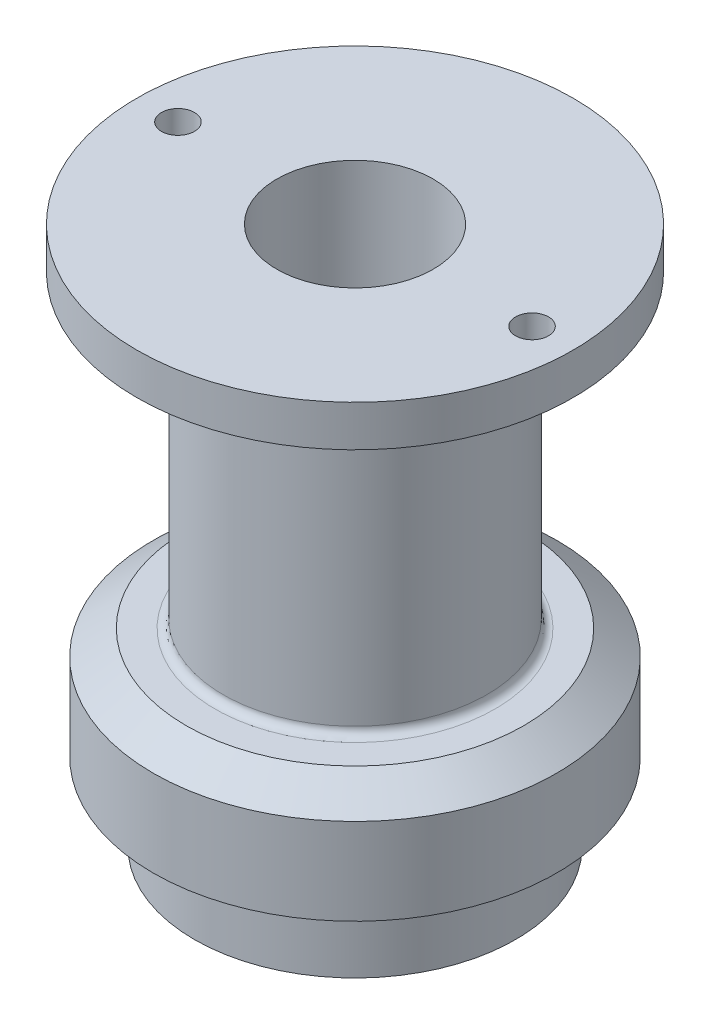
SolidWorks part; units mm, degrees
ref_plane "Front Plane" through (0, 0, 0) normal (0, 0, 1) x (1, 0, 0)
ref_plane "Top Plane" through (0, 0, 0) normal (0, 1, 0) x (1, 0, 0)
ref_plane "Right Plane" through (0, 0, 0) normal (1, 0, 0) x (0, 0, -1)
sketch "Sketch1" plane through (0, 0, 0) normal (0, 0, 1) x (1, 0, 0)
  line L0 (13.5, 0) -> (19.5, 0)
  line L1 (19.5, 0) -> (19.5, 8)
  line L2 (19.5, 8) -> (18, 8)
  line L3 (18, 8) -> (18, 9.5)
  line L4 (18, 9.5) -> (24.5, 9.5)
  line L5 (24.5, 9.5) -> (24.5, 20)
  line L6 (20.5, 23) -> (17, 23)
  line L7 (16, 24) -> (16, 59.5)
  line L8 (17, 60.5) -> (26.5, 60.5)
  line L9 (24.5, 20) -> (20.5, 23)
  line L10 (26.5, 60.5) -> (26.5, 65.5)
  line L11 (26.5, 65.5) -> (9.5, 65.5)
  line L12 (9.5, 65.5) -> (9.5, 48)
  line L13 (9.5, 48) -> (6.5, 44.5)
  line L14 (0, 0) -> (0, 87.6329) construction
  line L15 (6.5, 44.5) -> (6.5, 37.5)
  line L16 (7, 37) -> (7, 17)
  line L17 (7, 37) -> (6.5, 37.5)
  line L18 (6.5, 16.5) -> (6.5, 8)
  line L19 (7, 17) -> (6.5, 16.5)
  line L20 (6.5, 8) -> (13.5, 8)
  line L21 (13.5, 8) -> (13.5, 0)
  arc A0 (17, 23) -> (16, 24) centre (17, 24) cw
  arc A1 (16, 59.5) -> (17, 60.5) centre (17, 59.5) cw
  point P13 (16, 23)
  point P17 (16, 60.5)
  dimension "D12" = 1
  dimension "D14" = 1
  dimension "D1" = 13.5
  dimension "D2" = 6
  dimension "D3" = 8
  dimension "D4" = 1.5
  dimension "D5" = 1.5
  dimension "D6" = 6.5
  dimension "D7" = 10.5
  dimension "D8" = 3
  dimension "D9" = 4
  dimension "D10" = 4.5
  dimension "D11" = 37.5
  dimension "D13" = 10.5
  dimension "D15" = 5
  dimension "D16" = 17
  dimension "D17" = 17.5
  dimension "D18" = 0.5
  dimension "D19" = 0.5
  dimension "D20" = 7
  dimension "D21" = 6.5
  dimension "D22" = 20
  dimension "D23" = 0.5
  dimension "D24" = 8.5
  dimension "D25" = 7
  dimension "D26" = 8
revolve "Revolve1" add sketch "Sketch1" angle 360 about L14
sketch "Sketch2" plane through (0, 65.5, 0) normal (0, 1, 0) x (1, 0, 0)
  circle A0 centre (21.5, 0) radius 2
  circle A1 centre (-21.5, 0) radius 2
  dimension "D2" = 4
  dimension "D4" = 4
  dimension "D1" = 21.5
  dimension "D3" = 21.5
extrude "Cut-Extrude1" cut sketch "Sketch2" against normal blind 10
